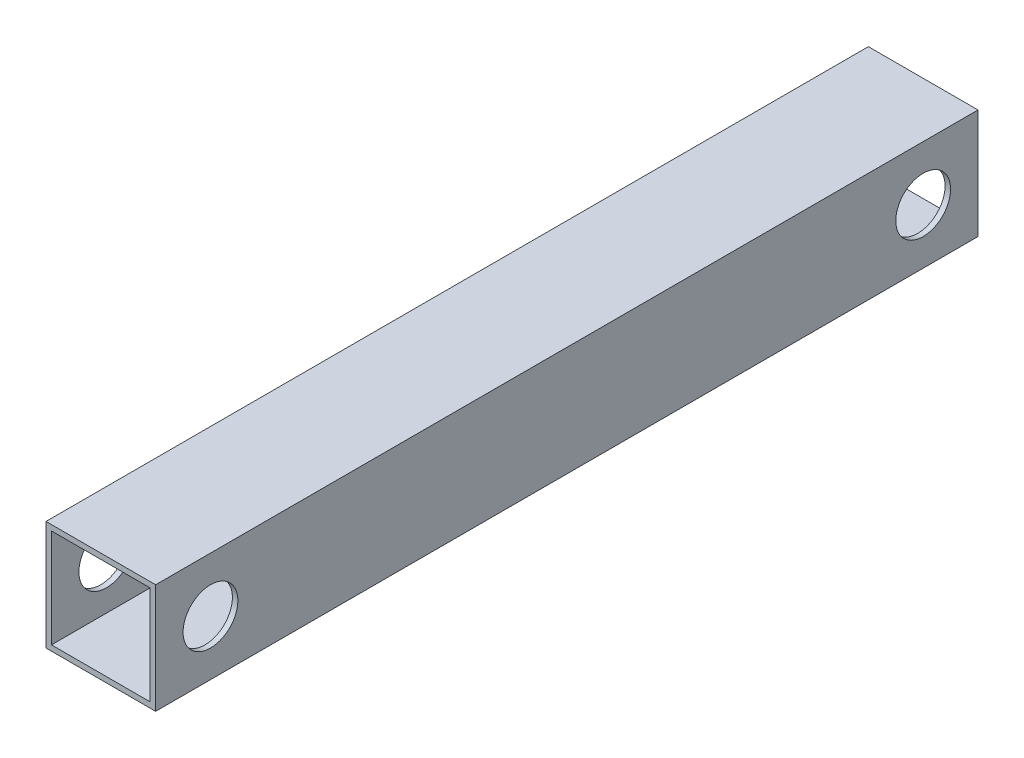
SolidWorks part; units mm, degrees
ref_plane "Front Plane" through (0, 0, 0) normal (0, 0, 1) x (1, 0, 0)
ref_plane "Top Plane" through (0, 0, 0) normal (0, 1, 0) x (1, 0, 0)
ref_plane "Right Plane" through (0, 0, 0) normal (1, 0, 0) x (0, 0, -1)
sketch "Sketch1" plane through (0, 0, 0) normal (0, 0, 1) x (1, 0, 0)
  line L1 (-10, -10) -> (10, -10)
  line L2 (-10, -10) -> (-10, 10)
  line L3 (-10, 10) -> (10, 10)
  line L4 (10, -10) -> (10, 10)
  line L5 (-10, -10) -> (10, 10) construction
  line L6 (-10, 10) -> (10, -10) construction
  line L7 (-9, 9) -> (9, 9)
  line L8 (-9, 9) -> (-9, -9)
  line L9 (-9, -9) -> (9, -9)
  line L10 (9, 9) -> (9, -9)
  line L11 (-9, 9) -> (9, -9) construction
  line L12 (-9, -9) -> (9, 9) construction
  point P0 (0, 0)
  point P6 (0, 0)
  dimension "D1" = 20
  dimension "D2" = 20
  dimension "D3" = 1
  dimension "D4" = 1
extrude "Boss-Extrude1" add sketch "Sketch1" along normal blind 150
sketch "Sketch2" plane through (10, 0, 0) normal (1, 0, 0) x (0, 0, -1)
  line L0 (-150, 0) -> (0, 0) construction
  line L1 (-150, -10) -> (-150, 10) construction
  line L2 (-75, 10) -> (-75, -10) construction
  line L3 (-150, 10) -> (0, 10) construction
  line L4 (-150, -10) -> (0, -10) construction
  circle A0 centre (-140, 0) radius 5
  circle A1 centre (-10, 0) radius 5
  dimension "D2" = 10
  dimension "D1" = 10
extrude "Cut-Extrude1" cut sketch "Sketch2" against normal blind 150
